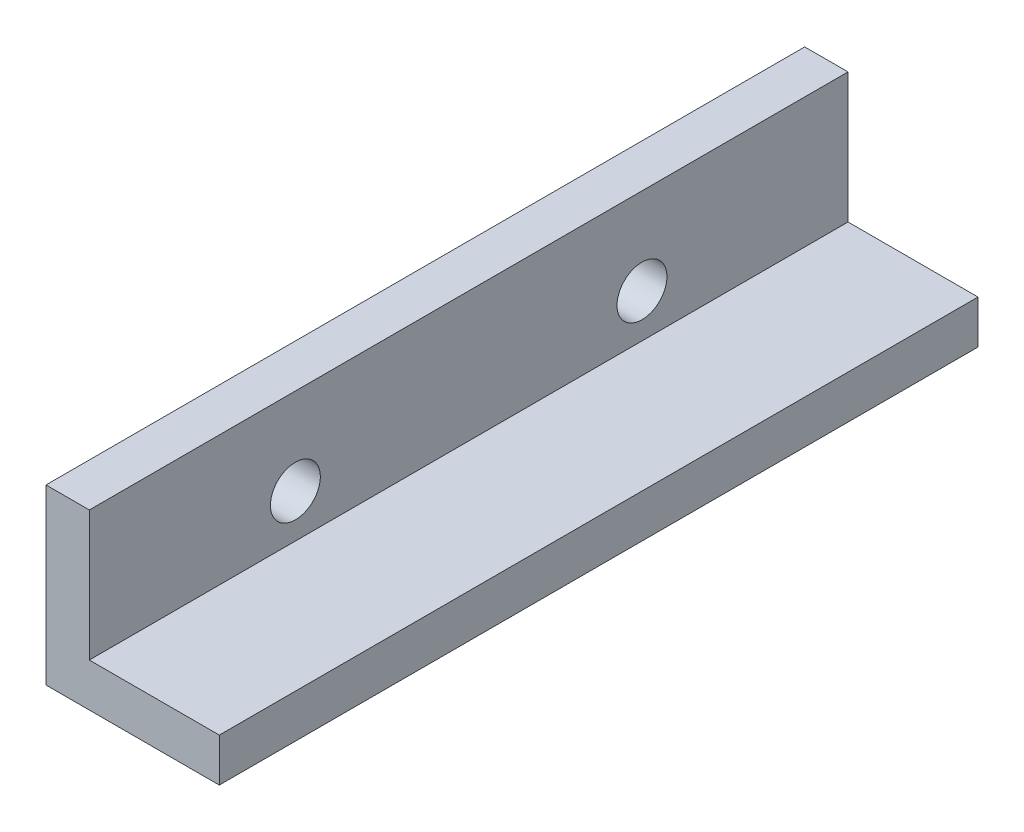
SolidWorks part; units mm, degrees
material "6061-T6 (SS)"
ref_plane "Front Plane" through (0, 0, 0) normal (0, 0, 1) x (1, 0, 0)
ref_plane "Top Plane" through (0, 0, 0) normal (0, 1, 0) x (1, 0, 0)
ref_plane "Right Plane" through (0, 0, 0) normal (1, 0, 0) x (0, 0, -1)
sketch "Sketch1" plane through (0, 0, 0) normal (0, 0, 1) x (1, 0, 0)
  line L0 (0, 12.7) -> (0, 0)
  line L1 (0, 0) -> (12.7, 0)
  line L2 (0, 12.7) -> (3.175, 12.7)
  line L3 (3.175, 12.7) -> (3.175, 3.175)
  line L4 (3.175, 3.175) -> (12.7, 3.175)
  line L5 (12.7, 3.175) -> (12.7, 0)
  dimension "D1" = 12.7
  dimension "D2" = 3.175
extrude "Boss-Extrude1" add sketch "Sketch1" along normal mid plane 55.6
sketch "Sketch2" plane through (0, 0, 0) normal (-1, 0, 0) x (0, 0, 1)
  line L0 (-27.8, 6.35) -> (27.8, 6.35) construction
  line L1 (-27.8, 12.7) -> (-27.8, 0) construction
  line L2 (27.8, 12.7) -> (27.8, 0) construction
  line L3 (-27.8, 12.7) -> (-27.8, 0) construction
  circle A1 centre (12.7, 6.35) radius 1.8288
  circle A2 centre (-12.7, 6.35) radius 1.8288
  dimension "D1" = 15.1
  dimension "D2" = 25.4
  dimension "D3" = 3.6576
extrude "Cut-Extrude1" cut sketch "Sketch2" against normal through all
